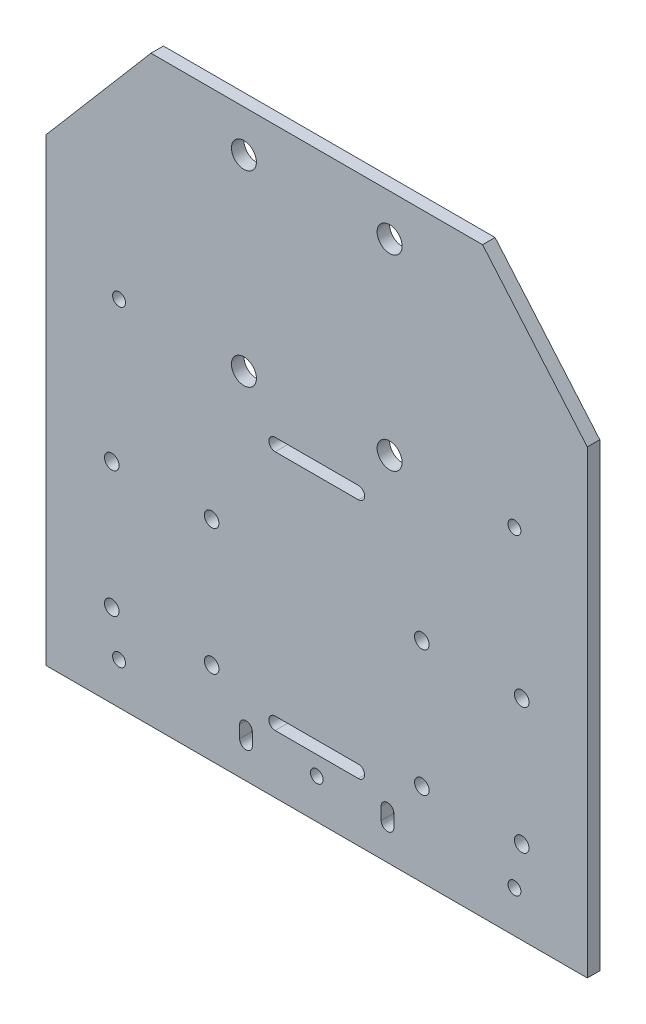
SolidWorks part; units mm, degrees
ref_plane "前视基准面" through (0, 0, 0) normal (0, 0, 1) x (1, 0, 0)
ref_plane "上视基准面" through (0, 0, 0) normal (0, 1, 0) x (1, 0, 0)
ref_plane "右视基准面" through (0, 0, 0) normal (1, 0, 0) x (0, 0, -1)
sketch "草图1" plane through (0, 0, 0) normal (0, 0, 1) x (1, 0, 0)
  line L0 (0, 0) -> (80.8163, 0) construction
  line L2 (65, -25) -> (65, 75.1634)
  line L4 (-65, -25) -> (-65, 75.1634)
  line L5 (22.0588, -25) -> (0, 0) construction
  line L6 (22.0588, 25) -> (-22.0588, -25) construction
  line L7 (0, 0) -> (0, -25) construction
  line L16 (-65, -25) -> (-65, -35.3324)
  line L22 (-65, -35.3324) -> (65, -35.3324)
  line L23 (0, -25) -> (0, 104.6676) construction
  line L24 (65, -35.3324) -> (65, -25)
  line L26 (65, 75.1634) -> (39.8402, 104.6676)
  line L29 (-39.8402, 104.6676) -> (39.8402, 104.6676)
  line L30 (-10, 38.1676) -> (10, 38.1676) construction
  line L31 (-10, 39.6676) -> (10, 39.6676)
  line L32 (-10, 36.6676) -> (10, 36.6676)
  line L33 (-10, -19.8324) -> (10, -19.8324) construction
  line L34 (-10, -18.3324) -> (10, -18.3324)
  line L35 (-10, -21.3324) -> (10, -21.3324)
  line L36 (-65, 75.1634) -> (-39.8402, 104.6676)
  circle A0 centre (49.25, -15.3324) radius 1.75
  circle A1 centre (25.25, -15.3324) radius 1.75
  circle A2 centre (25.25, 15) radius 1.75
  circle A3 centre (49.25, 15) radius 1.75
  circle A4 centre (-49.25, 15) radius 1.75
  circle A5 centre (-25.25, 15) radius 1.75
  circle A6 centre (-25.25, -15.3324) radius 1.75
  circle A7 centre (-49.25, -15.3324) radius 1.75
  circle A20 centre (-17.5, 94.6676) radius 3
  circle A21 centre (17.5, 94.6676) radius 3
  circle A22 centre (-17.5, 49.6676) radius 3
  circle A23 centre (17.5, 49.6676) radius 3
  arc A24 (-10, 39.6676) -> (-10, 36.6676) centre (-10, 38.1676) ccw
  arc A25 (10, 36.6676) -> (10, 39.6676) centre (10, 38.1676) ccw
  arc A26 (-10, -18.3324) -> (-10, -21.3324) centre (-10, -19.8324) ccw
  arc A27 (10, -21.3324) -> (10, -18.3324) centre (10, -19.8324) ccw
  point P0 (0, 0)
  point P34 (0, 38.1676)
  point P35 (0, 105)
  point P53 (0, -19.8324)
  dimension "D3" = 3.5
  dimension "D4" = 15.75
  dimension "D8" = 6
  dimension "D9" = 35
  dimension "D11" = 10
  dimension "D16" = 1.5
  dimension "D17" = 10
  dimension "D2" = 140
  dimension "D5" = 130
  dimension "D12" = 15.75
  dimension "D13" = 15.75
  dimension "D14" = 20
  dimension "D15" = 17.5
  dimension "10" = 10
  dimension "D18" = 20
  dimension "D6" = 2
  dimension "D7" = 2
  dimension "D10" = 2
  dimension "D19" = 2
extrude "凸台-拉伸1" add sketch "草图1" along normal blind 3
sketch "草图3" plane through (0, 0, 0) normal (0, 0, -1) x (-1, 0, 0)
  line L4 (0, -28.2742) -> (0, 166.1841) construction
  line L6 (-17, -27.3324) -> (-17, -24.3324) construction
  line L7 (-18.52, -27.3324) -> (-18.52, -24.3324)
  line L8 (-15.48, -27.3324) -> (-15.48, -24.3324)
  line L9 (65, -35.3324) -> (-65, -35.3324) construction
  line L10 (17, -27.3324) -> (17, -24.3324) construction
  line L11 (18.52, -27.3324) -> (18.52, -24.3324)
  line L12 (15.48, -27.3324) -> (15.48, -24.3324)
  arc A5 (-18.52, -27.3324) -> (-15.48, -27.3324) centre (-17, -27.3324) ccw
  arc A6 (-15.48, -24.3324) -> (-18.52, -24.3324) centre (-17, -24.3324) ccw
  arc A7 (18.52, -27.3324) -> (15.48, -27.3324) centre (17, -27.3324) cw
  arc A8 (15.48, -24.3324) -> (18.52, -24.3324) centre (17, -24.3324) cw
  circle A9 centre (0, -25.8324) radius 1.525
  point P2 (-18, 97.8359)
  point P3 (-17, -25.8324)
  point P13 (18, 97.8359)
  point P15 (17, -25.8324)
  dimension "D1" = 1.52
  dimension "D3" = 8
  dimension "D5" = 3.05
  dimension "D2" = 17
  dimension "D4" = 3
  dimension "D6" = 17
extrude "切除-拉伸2" cut sketch "草图3" against normal blind 10
sketch "草图5" plane through (0, 0, 3) normal (0, 0, 1) x (1, 0, 0)
  line L0 (0, -35.3324) -> (0, 63.5951) construction
  line L1 (39.8402, 104.6676) -> (-39.8402, 104.6676) construction
  line L3 (-65, -35.3324) -> (65, -35.3324) construction
  circle A0 centre (-47.5, 49.6676) radius 1.55
  circle A1 centre (47.5, 49.6676) radius 1.55
  circle A2 centre (-47.5, -25.3324) radius 1.55
  circle A3 centre (47.5, -25.3324) radius 1.55
  dimension "D1" = 3.1
  dimension "D2" = 47.5
  dimension "D3" = 2
  dimension "D4" = 130
  dimension "D5" = 75
  dimension "D6" = 47.5
  dimension "D7" = 75
  dimension "D8" = 10
extrude "切除-拉伸3" cut sketch "草图5" against normal blind 10
